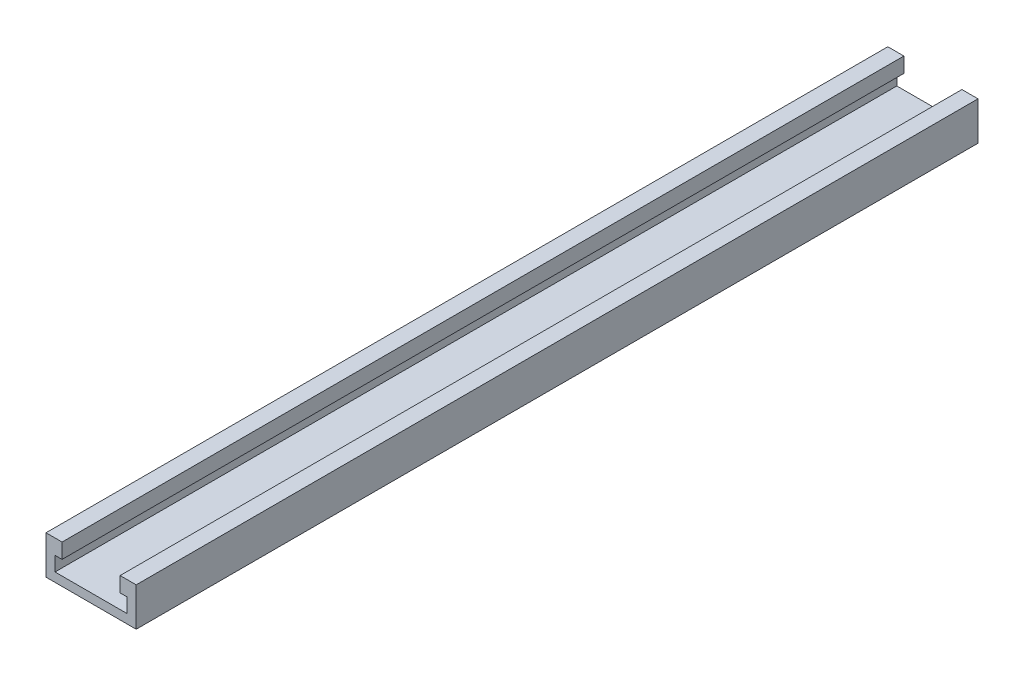
SolidWorks part; units mm, degrees
ref_plane "Plan de face" through (0, 0, 0) normal (0, 0, 1) x (1, 0, 0)
ref_plane "Plan de dessus" through (0, 0, 0) normal (0, 1, 0) x (1, 0, 0)
ref_plane "Plan de droite" through (0, 0, 0) normal (1, 0, 0) x (0, 0, -1)
sketch "Esquisse1" plane through (0, 0, 0) normal (0, 0, 1) x (1, 0, 0)
  line L0 (-15, 0) -> (15, 0)
  line L1 (15, 0) -> (15, 12.8)
  line L2 (15, 12.8) -> (9.65, 12.8)
  line L3 (9.65, 12.8) -> (9.65, 7.8)
  line L4 (9.65, 7.8) -> (12, 7.8)
  line L5 (12, 7.8) -> (12, 3)
  line L6 (12, 3) -> (-12, 3)
  line L7 (0, 0) -> (0, 3) construction
  line L8 (-12, 7.8) -> (-12, 3)
  line L9 (-9.65, 7.8) -> (-12, 7.8)
  line L10 (-9.65, 12.8) -> (-9.65, 7.8)
  line L11 (-15, 12.8) -> (-9.65, 12.8)
  line L12 (-15, 0) -> (-15, 12.8)
  dimension "D1" = 30
  dimension "D2" = 12.8
  dimension "D3" = 5
  dimension "D4" = 4.8
  dimension "D5" = 24
  dimension "D6" = 19.3
extrude "Boss.-Extru.1" add sketch "Esquisse1" along normal blind 280
